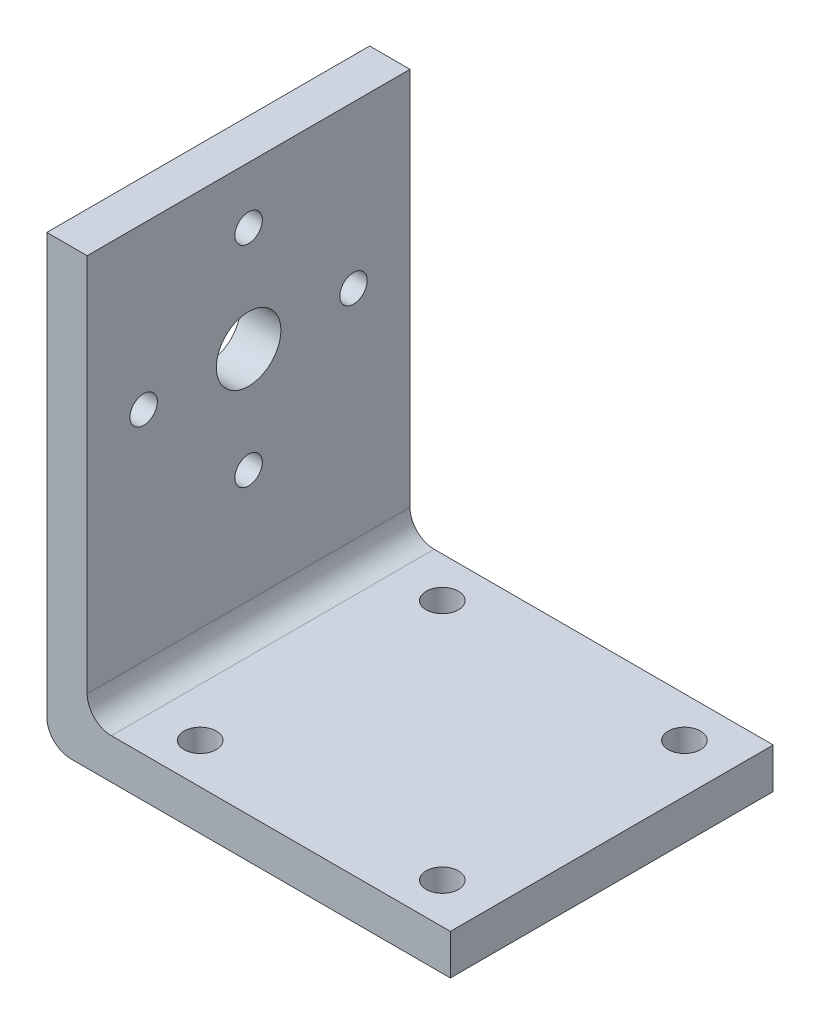
SolidWorks part; units mm, degrees
ref_plane "Front Plane" through (0, 0, 0) normal (0, 0, 1) x (1, 0, 0)
ref_plane "Top Plane" through (0, 0, 0) normal (0, 1, 0) x (1, 0, 0)
ref_plane "Right Plane" through (0, 0, 0) normal (1, 0, 0) x (0, 0, -1)
sketch "Sketch1" plane through (0, 0, 0) normal (0, 1, 0) x (1, 0, 0)
  line L1 (0, 0) -> (50, 0)
  line L2 (0, 0) -> (0, -40)
  line L3 (0, -40) -> (50, -40)
  line L4 (50, 0) -> (50, -40)
  dimension "D1" = 50
  dimension "D2" = 40
extrude "Boss-Extrude1" add sketch "Sketch1" along normal blind 5
sketch "Sketch2" plane through (0, 5, 0) normal (0, 1, 0) x (1, 0, 0)
  line L1 (0, 0) -> (5, 0)
  line L2 (0, 0) -> (0, -40)
  line L3 (0, -40) -> (5, -40)
  line L4 (5, 0) -> (5, -40)
  dimension "D1" = 5
  dimension "D2" = 40
extrude "Boss-Extrude2" add sketch "Sketch2" along normal blind 50
fillet "Fillet1" radius 3 2 edges at (0, 0, 20) (5, 5, 20)
sketch "Sketch3" plane through (0, 0, 0) normal (-1, 0, 0) x (0, 0, 1)
  circle A0 centre (20, 35) radius 4
  dimension "D1" = 8
extrude "Cut-Extrude1" cut sketch "Sketch3" against normal up to next
sketch "Sketch5" plane through (0, 0, 0) normal (-1, 0, 0) x (0, 0, 1)
  line L0 (0, 55) -> (40, 55) construction
  line L1 (0, 55) -> (0, 3) construction
  circle A0 centre (7, 35) radius 1.7
  circle A1 centre (33, 35) radius 1.7
  circle A3 centre (20, 48) radius 1.7
  circle A4 centre (20, 22) radius 1.7
  dimension "D1" = 3.4
  dimension "D2" = 3.4
  dimension "D3" = 26
  dimension "D6" = 3.4
  dimension "D7" = 3.4
  dimension "D8" = 26
  dimension "D9" = 20
  dimension "D10" = 7
  dimension "D4" = 20
  dimension "D5" = 7
extrude "Cut-Extrude2" cut sketch "Sketch5" against normal up to next
sketch "Sketch6" plane through (0, 5, 0) normal (0, 1, 0) x (1, 0, 0)
  line L0 (50, 0) -> (8, 0) construction
  line L1 (50, -40) -> (50, 0) construction
  circle A0 centre (14, -5) radius 2
  circle A1 centre (14, -35) radius 2
  circle A2 centre (44, -5) radius 2
  circle A3 centre (44, -35) radius 2
  dimension "D1" = 4
  dimension "D2" = 4
  dimension "D3" = 4
  dimension "D4" = 4
  dimension "D5" = 30
  dimension "D6" = 30
  dimension "D7" = 30
  dimension "D9" = 6
  dimension "D8" = 5
  dimension "D10" = 6
extrude "Cut-Extrude3" cut sketch "Sketch6" against normal up to next
